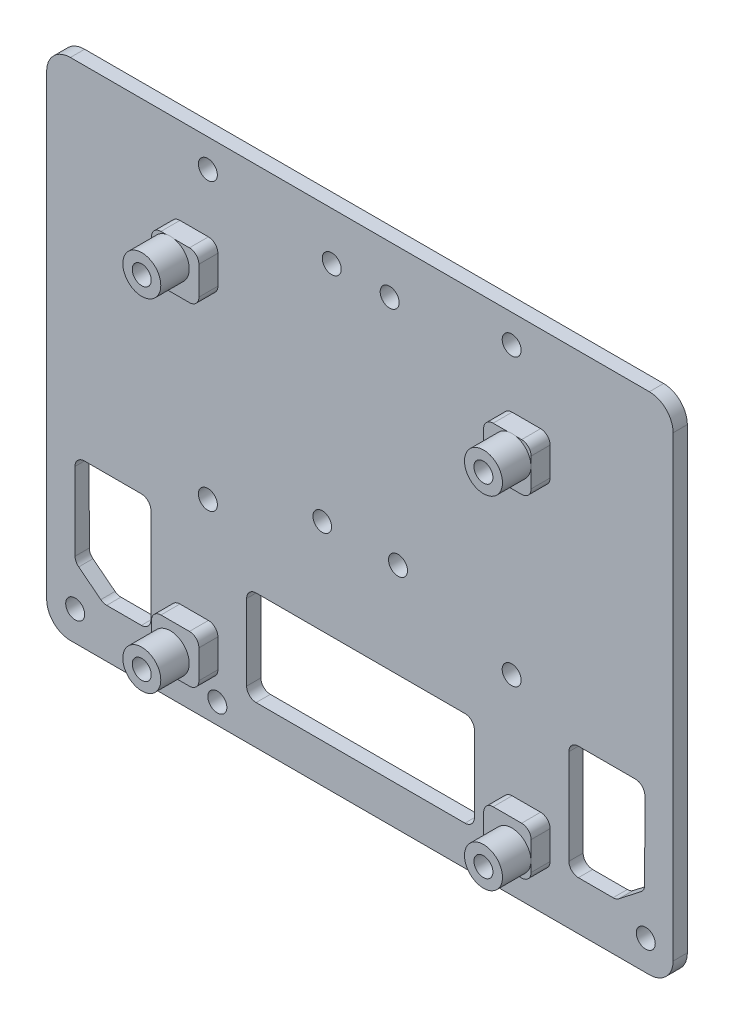
SolidWorks part; units mm, degrees
ref_plane "Front Plane" through (0, 0, 0) normal (0, 0, 1) x (1, 0, 0)
ref_plane "Top Plane" through (0, 0, 0) normal (0, 1, 0) x (1, 0, 0)
ref_plane "Right Plane" through (0, 0, 0) normal (1, 0, 0) x (0, 0, -1)
other "Graphic1"
other "object_1 (Open) -1"
ref_plane "Plane1" through (0, 0, 10) normal (0, 0, 1) x (1, 0, 0)
sketch "Sketch1" plane through (0, 0, 10) normal (0, 0, 1) x (1, 0, 0)
  line L1 (144.9639, 320.0391) -> (210.9639, 320.0391)
  line L2 (144.9639, 320.0391) -> (144.9639, 266.8391)
  line L3 (144.9639, 266.8391) -> (210.9639, 266.8391)
  line L4 (210.9639, 320.0391) -> (210.9639, 266.8391)
  circle A0 centre (161.9475, 317.0605) radius 1
  circle A1 centre (193.9565, 317.0605) radius 1
  circle A2 centre (174.9978, 314.9828) radius 1
  circle A3 centre (181.1009, 314.9828) radius 1
  circle A4 centre (173.9978, 290.9653) radius 0.9833
  circle A5 centre (181.9833, 290.9653) radius 1
  circle A6 centre (161.9475, 286.9627) radius 1
  circle A7 centre (193.9565, 286.9627) radius 1
  circle A8 centre (162.9475, 268.9705) radius 1
  circle A9 centre (192.9565, 268.9705) radius 1.0113
  circle A10 centre (208.0846, 269.9818) radius 1
  circle A11 centre (147.9666, 269.9705) radius 1
  dimension "D1" = 66
  dimension "D2" = 53.2
extrude "Boss-Extrude1" add sketch "Sketch1" along normal blind 1.5
sketch "Sketch2" plane through (0, 0, 11.5) normal (0, 0, 1) x (1, 0, 0)
  line L0 (193.0042, 310.9393) -> (193.0042, 305.9393)
  line L1 (158.0042, 310.9393) -> (163.0042, 310.9393)
  line L2 (158.0042, 310.9393) -> (158.0042, 305.9393)
  line L3 (158.0042, 305.9393) -> (163.0042, 305.9393)
  line L4 (163.0042, 310.9393) -> (163.0042, 305.9393)
  line L5 (193.0042, 310.9393) -> (198.0042, 310.9393)
  line L6 (198.0042, 310.9393) -> (198.0042, 305.9393)
  line L7 (193.0042, 305.9393) -> (198.0042, 305.9393)
  line L8 (193.0042, 275.9393) -> (193.0042, 270.9393)
  line L9 (193.0042, 275.9393) -> (198.0042, 275.9393)
  line L10 (198.0042, 275.9393) -> (198.0042, 270.9393)
  line L11 (193.0042, 270.9393) -> (198.0042, 270.9393)
  line L12 (158.0042, 275.9393) -> (158.0042, 270.9393)
  line L13 (158.0042, 275.9393) -> (163.0042, 275.9393)
  line L14 (163.0042, 275.9393) -> (163.0042, 270.9393)
  line L15 (158.0042, 270.9393) -> (163.0042, 270.9393)
  dimension "D1" = 5
  dimension "D2" = 5
  dimension "D3" = 2
  dimension "D4" = 2
extrude "Boss-Extrude2" add sketch "Sketch2" along normal blind 2
fillet "Fillet1" radius 1 16 edges at (158.0042, 275.9393, 12.5) (163.0042, 275.9393, 12.5) (163.0042, 270.9393, 12.5) (158.0042, 270.9393, 12.5) (198.0042, 275.9393, 12.5) (193.0042, 275.9393, 12.5) (198.0042, 270.9393, 12.5) (193.0042, 270.9393, 12.5) (193.0042, 305.9393, 12.5) (193.0042, 310.9393, 12.5) (198.0042, 305.9393, 12.5) (198.0042, 310.9393, 12.5) (158.0042, 310.9393, 12.5) (163.0042, 310.9393, 12.5) (163.0042, 305.9393, 12.5) (158.0042, 305.9393, 12.5)
fillet "Fillet2" radius 2.5 4 edges at (144.9639, 320.0391, 10.75) (210.9639, 320.0391, 10.75) (210.9639, 266.8391, 10.75) (144.9639, 266.8391, 10.75)
sketch "Sketch3" plane through (0, 0, 13.5) normal (0, 0, 1) x (1, 0, 0)
  circle A0 centre (159.9868, 308.9933) radius 2
  circle A1 centre (195.9868, 308.9933) radius 2
  circle A2 centre (195.9868, 272.9933) radius 2
  circle A3 centre (159.9868, 272.9933) radius 2
  point P2 (169.9868, 308.9933)
  dimension "D1" = 2
  dimension "D2" = 2
extrude "Boss-Extrude3" add sketch "Sketch3" along normal blind 3
sketch "Sketch4" plane through (0, 0, 16.5) normal (0, 0, 1) x (1, 0, 0)
  circle A0 centre (159.9799, 308.9671) radius 1
  circle A1 centre (195.9799, 308.9671) radius 1
  circle A2 centre (195.9799, 272.9671) radius 1
  circle A3 centre (159.9799, 272.9671) radius 1
  point P6 (169.9799, 308.9671)
  point P7 (169.9799, 308.9671)
  point P8 (159.9799, 298.9671)
  dimension "D1" = 2
  dimension "D2" = 2
extrude "Cut-Extrude1" cut sketch "Sketch4" against normal through all
sketch "Sketch5" plane through (0, 0, 11.5) normal (0, 0, 1) x (1, 0, 0)
  line L0 (199.987, 283.9594) -> (207.987, 283.9594)
  line L1 (207.987, 283.9594) -> (207.9709, 274.2894)
  line L2 (207.9709, 274.2894) -> (204.987, 271.9594)
  line L3 (204.987, 271.9594) -> (199.987, 271.9594)
  line L4 (199.987, 271.9594) -> (199.987, 283.9594)
  line L5 (177.9639, 266.8391) -> (177.9639, 261.7896) construction
  line L6 (147.4639, 266.8391) -> (208.4639, 266.8391) construction
  line L7 (150.9409, 271.9594) -> (155.9409, 271.9594)
  line L8 (147.957, 274.2894) -> (150.9409, 271.9594)
  line L9 (147.9409, 283.9594) -> (147.957, 274.2894)
  line L10 (155.9409, 283.9594) -> (147.9409, 283.9594)
  line L11 (155.9409, 271.9594) -> (155.9409, 283.9594)
  line L13 (166.0306, 280.9606) -> (190.0306, 280.9606)
  line L14 (166.0306, 280.9606) -> (166.0306, 270.9606)
  line L15 (166.0306, 270.9606) -> (190.0306, 270.9606)
  line L16 (190.0306, 280.9606) -> (190.0306, 270.9606)
  dimension "D1" = 8
  dimension "D2" = 9.67
  dimension "D3" = 5
  dimension "D4" = 12
  dimension "D5" = 24
  dimension "D6" = 10
extrude "Cut-Extrude2" cut sketch "Sketch5" against normal blind 3
fillet "Fillet3" radius 1 14 edges at (190.0306, 270.9606, 10.75) (166.0306, 270.9606, 10.75) (166.0306, 280.9606, 10.75) (190.0306, 280.9606, 10.75) (147.957, 274.2894, 10.75) (147.9409, 283.9594, 10.75) (155.9409, 283.9594, 10.75) (155.9409, 271.9594, 10.75) (150.9409, 271.9594, 10.75) (204.987, 271.9594, 10.75) (207.9709, 274.2894, 10.75) (207.987, 283.9594, 10.75) (199.987, 271.9594, 10.75) (199.987, 283.9594, 10.75)
